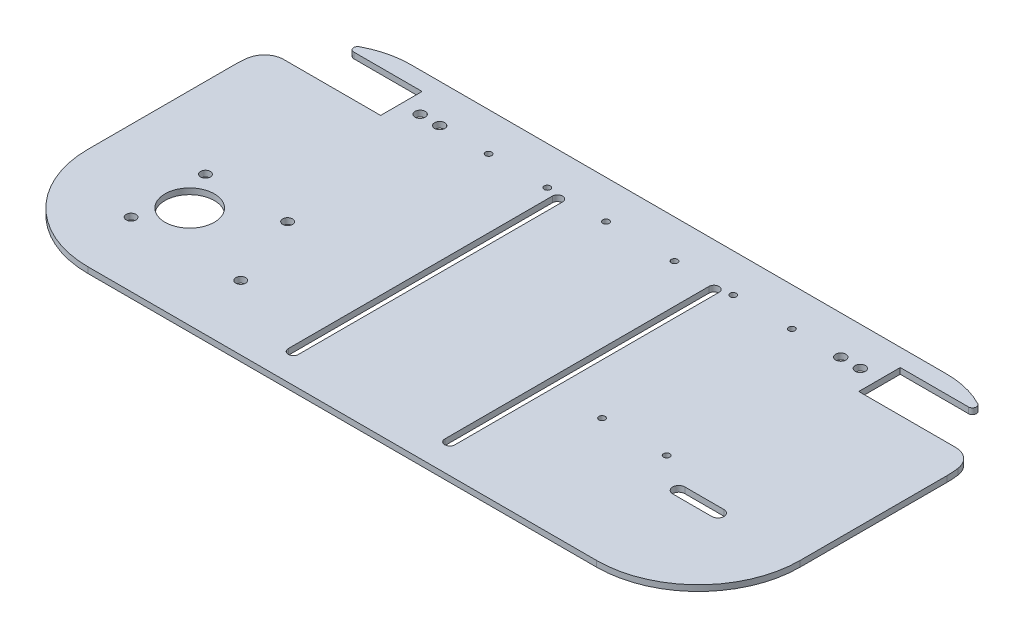
SolidWorks part; units mm, degrees
ref_plane "Front Plane" through (0, 0, 0) normal (0, 0, 1) x (1, 0, 0)
ref_plane "Top Plane" through (0, 0, 0) normal (0, 1, 0) x (1, 0, 0)
ref_plane "Right Plane" through (0, 0, 0) normal (1, 0, 0) x (0, 0, -1)
sketch "Sketch1" plane through (0, 0, 0) normal (0, 1, 0) x (1, 0, 0)
  line L0 (0, 0) -> (260, 0) construction
  line L5 (0, 52) -> (260, 52)
  line L6 (0, -52) -> (260, -52)
  line L7 (270, 0) -> (250, 0) construction
  line L8 (270, -3.1) -> (250, -3.1)
  line L9 (270, 3.1) -> (250, 3.1)
  line L11 (-52, 0) -> (312, 0) construction
  line L12 (-52, 0) -> (-52, 120)
  line L13 (-52, 120) -> (312, 120)
  line L14 (312, 0) -> (312, 120)
  arc A0 (0, 52) -> (0, -52) centre (0, 0) ccw
  arc A1 (260, -52) -> (260, 52) centre (260, 0) ccw
  circle A2 centre (0, 0) radius 3.1
  arc A4 (270, -3.1) -> (270, 3.1) centre (270, 0) ccw
  arc A5 (250, 3.1) -> (250, -3.1) centre (250, 0) ccw
  point P2 (130, 0)
  point P12 (260, 0)
  dimension "D2" = 52
  dimension "D3" = 6.2
  dimension "D1" = 260
  dimension "D4" = 20
  dimension "D5" = 120
  dimension "D6" = 270
extrude "Boss-Extrude1" add sketch "Sketch1" along normal blind 3 contours L6 A1 L5 A0 A5 L9 A4 L8 A2 | A1 L14 L13 L12 A0 L5
sketch "Sketch2" plane through (0, 3, 0) normal (0, 1, 0) x (1, 0, 0)
  line L0 (-52, 105) -> (312, 105) construction
  line L1 (-52, 0) -> (-52, 120) construction
  line L2 (312, 0) -> (312, 120) construction
  line L3 (-52, 120) -> (312, 120) construction
  line L4 (130, 120) -> (130, -52) construction
  line L5 (0, -52) -> (260, -52) construction
  line L6 (90, 120) -> (90, -52) construction
  line L7 (170, 120) -> (170, -52) construction
  line L11 (-36.5377, -37) -> (296.5377, -37) construction
  line L12 (90, -37) -> (90, 98) construction
  line L13 (87.4, -37) -> (87.4, 98)
  line L14 (92.6, -37) -> (92.6, 98)
  line L15 (170, -37) -> (170, 98) construction
  line L16 (172.6, -37) -> (172.6, 98)
  line L17 (167.4, -37) -> (167.4, 98)
  arc A2 (-52, 0) -> (0, -52) centre (0, 0) ccw construction
  arc A3 (260, -52) -> (312, 0) centre (260, 0) ccw construction
  arc A4 (87.4, -37) -> (92.6, -37) centre (90, -37) ccw
  arc A5 (92.6, 98) -> (87.4, 98) centre (90, 98) ccw
  arc A6 (172.6, -37) -> (167.4, -37) centre (170, -37) cw
  arc A7 (167.4, 98) -> (172.6, 98) centre (170, 98) cw
  point P33 (90, 30.5)
  point P40 (170, 30.5)
  dimension "D4" = 2.6
  dimension "D1" = 15
  dimension "D2" = 40
  dimension "D3" = 40
  dimension "D6" = 15
  dimension "D7" = 135
extrude "Cut-Extrude1" cut sketch "Sketch2" against normal through all
fillet "Fillet1" radius 45 2 edges at (312, 1.5, -120) (-52, 1.5, -120)
sketch "Sketch3" plane through (0, 3, 0) normal (0, 1, 0) x (1, 0, 0)
  circle A0 centre (0, 0) radius 12.6
  dimension "D1" = 25.2
extrude "Cut-Extrude2" cut sketch "Sketch3" against normal through all
sketch "Sketch4" plane through (0, 3, 0) normal (0, 1, 0) x (1, 0, 0)
  circle A0 centre (-10.9389, 19) radius 2.5
  circle A1 centre (31.0611, 19) radius 2.5
  circle A2 centre (45.07, -19) radius 2.5
  circle A3 centre (-10.9389, -19) radius 2.5
  circle A4 centre (-10.9389, 19) radius 2.5 construction
  circle A5 centre (-10.9389, -19) radius 2.5 construction
  point P12 (51.2269, -23.8127)
  point P13 (0, 0)
  point P14 (31.0611, 19)
  point P15 (45.07, -19)
sketch "Sketch5" plane through (0, 3, 0) normal (0, 1, 0) x (1, 0, 0)
  line L0 (260, -52) -> (260, 120) construction
  line L1 (-7, 120) -> (267, 120) construction
  line L2 (-52, 0) -> (-52, 75) construction
  line L3 (0, -52) -> (260, -52) construction
  line L4 (0, -52) -> (0, 120) construction
  line L5 (-7.6, 108) -> (7.6, 108)
  line L6 (-7.6, 108) -> (-7.6, 92.8)
  line L7 (-7.6, 92.8) -> (7.6, 92.8)
  line L8 (7.6, 108) -> (7.6, 92.8)
  line L9 (252.4, 108) -> (267.6, 108)
  line L10 (252.4, 108) -> (252.4, 92.8)
  line L11 (252.4, 92.8) -> (267.6, 92.8)
  line L12 (267.6, 108) -> (267.6, 92.8)
  line L13 (-7.6, 92.8) -> (-52, 92.8)
  line L14 (-7.6, 92.8) -> (-7.6, 108)
  line L15 (-7.6, 108) -> (-52, 108)
  line L16 (-52, 92.8) -> (-52, 108)
  line L17 (130, 120) -> (130, -52) construction
  line L18 (7.6, 92.8) -> (22.6, 92.8)
  line L19 (7.6, 92.8) -> (7.6, 108)
  line L20 (7.6, 108) -> (22.6, 108)
  line L21 (22.6, 92.8) -> (22.6, 108)
  line L22 (-52, 108) -> (22.6, 108)
  line L23 (-52, 108) -> (-52, 111)
  line L24 (-52, 111) -> (22.6, 111)
  line L25 (22.6, 108) -> (22.6, 111)
  line L26 (-52, 92.8) -> (22.6, 92.8)
  line L27 (-52, 92.8) -> (-52, 89.8)
  line L28 (-52, 89.8) -> (22.6, 89.8)
  line L29 (22.6, 92.8) -> (22.6, 89.8)
  line L30 (312, 89.8) -> (237.4, 89.8)
  line L31 (237.4, 92.8) -> (237.4, 89.8)
  line L32 (312, 92.8) -> (237.4, 92.8)
  line L33 (312, 92.8) -> (312, 89.8)
  line L34 (312, 111) -> (237.4, 111)
  line L35 (237.4, 108) -> (237.4, 111)
  line L36 (312, 108) -> (237.4, 108)
  line L37 (312, 108) -> (312, 111)
  line L38 (252.4, 108) -> (237.4, 108)
  line L39 (237.4, 92.8) -> (237.4, 108)
  line L40 (252.4, 92.8) -> (237.4, 92.8)
  line L41 (252.4, 92.8) -> (252.4, 108)
  line L42 (267.6, 108) -> (312, 108)
  line L43 (312, 92.8) -> (312, 108)
  line L44 (267.6, 92.8) -> (312, 92.8)
  line L45 (267.6, 92.8) -> (267.6, 108)
  line L46 (7.8, 111) -> (7.8, 89.8)
  line L47 (252.2, 111) -> (252.2, 89.8)
  arc A0 (260, -52) -> (312, 0) centre (260, 0) ccw construction
  arc A1 (-52, 0) -> (0, -52) centre (0, 0) ccw construction
  point P24 (0, 108)
  point P25 (260, 108)
  arc M25 (312, 75) -> (267, 120) centre (267, 75) ccw
  arc M27 (-7, 120) -> (-52, 75) centre (-7, 75) ccw
  dimension "D1" = 15.2
  dimension "D2" = 12
  dimension "D3" = 15
  dimension "D4" = 3
  dimension "D5" = 0.2
  dimension "D6" = 0.2
extrude "Cut-Extrude4" cut sketch "Sketch5" against normal through all contours L24 L23 L15 M27 | L6 L15 L13 M27 | L46 L18 L7 L13 L28 M27 | L46 L20 L8 L18 | L46 L24 L15 L5 L20 M27 | L8 L5 L6 L7 | L16 L13 L15 M27 | L27 L28 L13 M27 | L34 L47 L36 L9 M25 | L36 L47 L32 L10 | L12 L9 L10 L11 | L32 L47 L30 L11 M25 | L36 L12 L32 M25
fillet "Fillet3" radius 2 2 edges at (-34, 1.5, -111) (294, 1.5, -111)
fillet "Fillet4" radius 10 2 edges at (309.4966, 1.5, -89.8) (-49.4966, 1.5, -89.8)
extrude "Cut-Extrude5" cut sketch "Sketch4" against normal blind 10
sketch "Sketch7" plane through (0, 3, 0) normal (0, 1, 0) x (1, 0, 0)
  circle A0 centre (17.4, 100.4) radius 2.6
  circle A1 centre (27.4, 100.4) radius 2.6
  circle A2 centre (82.4, 100.4) radius 1.6
  circle A3 centre (112.4, 100.4) radius 1.6
  circle A4 centre (147.4, 100.4) radius 1.6
  circle A5 centre (177.4, 100.4) radius 1.6
  circle A6 centre (207.4, 100.4) radius 1.6
  circle A7 centre (232.4, 100.4) radius 2.6
  circle A8 centre (242.4, 100.4) radius 2.6
  circle A9 centre (52.4, 100.4) radius 1.6
  dimension "D1" = 5.2
  dimension "D2" = 5.2
  dimension "D3" = 3.2
extrude "Cut-Extrude6" cut sketch "Sketch7" against normal through all
sketch "Sketch8" plane through (0, 3, 0) normal (0, 1, 0) x (1, 0, 0)
  circle A0 centre (231.4, 12.4) radius 1.6
  circle A1 centre (198.4, 12.4) radius 1.6
  dimension "D1" = 3.2
extrude "Cut-Extrude7" cut sketch "Sketch8" against normal through all
